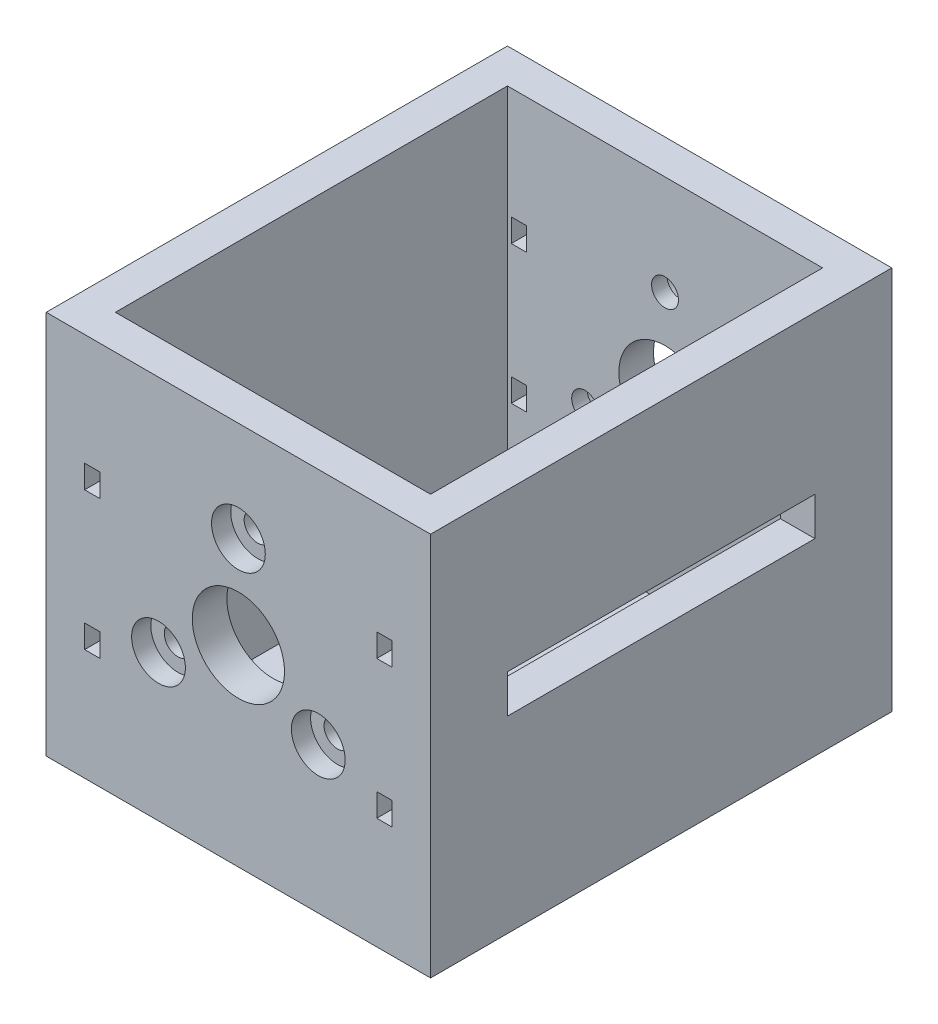
SolidWorks part; units mm, degrees
ref_plane "Front Plane" through (0, 0, 0) normal (0, 0, 1) x (1, 0, 0)
ref_plane "Top Plane" through (0, 0, 0) normal (0, 1, 0) x (1, 0, 0)
ref_plane "Right Plane" through (0, 0, 0) normal (1, 0, 0) x (0, 0, -1)
sketch "Sketch1" plane through (0, 0, 0) normal (0, 0, 1) x (1, 0, 0)
  line L1 (25, -25) -> (-25, -25)
  line L2 (25, -25) -> (25, 25)
  line L3 (25, 25) -> (-25, 25)
  line L4 (-25, -25) -> (-25, 25)
  line L5 (25, -25) -> (-25, 25) construction
  line L6 (25, 25) -> (-25, -25) construction
  point P0 (0, 0)
  dimension "D1" = 50
  dimension "D2" = 50
extrude "Boss-Extrude1" add sketch "Sketch1" along normal mid plane 60
ref_plane "Plane1" through (0, 0, 30) normal (0, 0, 1) x (1, 0, 0)
sketch "Sketch3" plane through (0, 0, 30) normal (0, 0, 1) x (1, 0, 0)
  circle A0 centre (0, 0) radius 6
  dimension "D1" = 12
extrude "Cut-Extrude1" cut sketch "Sketch3" against normal blind 70
sketch "Sketch4" plane through (0, 0, 30) normal (0, 0, 1) x (1, 0, 0)
  line L0 (-23.4706, 0) -> (22.7036, 0) construction
  line L1 (0, 23.8924) -> (0, -23.1254) construction
  line L3 (12, -0.5) -> (17, -0.5)
  line L4 (12, -0.5) -> (12, 0.5)
  line L5 (12, 0.5) -> (17, 0.5)
  line L6 (17, -0.5) -> (17, 0.5)
  line L7 (12, -0.5) -> (17, 0.5) construction
  line L8 (12, 0.5) -> (17, -0.5) construction
  point P5 (14.5, 0)
  dimension "D1" = 5
  dimension "D2" = 1
  dimension "D3" = 12
extrude "Cut-Extrude2" [suppressed] cut sketch "Sketch4" against normal blind 70
pattern_circular "CirPattern1" [suppressed] count 4 over 360
ref_plane "Plane2" through (0, 25, 0) normal (0, 1, 0) x (1, 0, 0)
sketch "Sketch5" plane through (0, 25, 0) normal (0, 1, 0) x (1, 0, 0)
  line L1 (20.5, -25.5) -> (-20.5, -25.5)
  line L2 (20.5, -25.5) -> (20.5, 25.5)
  line L3 (20.5, 25.5) -> (-20.5, 25.5)
  line L4 (-20.5, -25.5) -> (-20.5, 25.5)
  line L5 (20.5, -25.5) -> (-20.5, 25.5) construction
  line L6 (20.5, 25.5) -> (-20.5, -25.5) construction
  point P0 (0, 0)
  dimension "D1" = 41
  dimension "D2" = 51
extrude "Cut-Extrude3" cut sketch "Sketch5" against normal blind 48
sketch "Sketch6" plane through (0, 0, 30) normal (0, 0, 1) x (1, 0, 0)
  line L0 (0, 21.2323) -> (0, -19.4194) construction
  line L1 (-20.012, 0) -> (20.9882, 0) construction
  circle A0 centre (10, 0) radius 1.75
  dimension "D1" = 3.5
  dimension "D2" = 10
extrude "Cut-Extrude4" [suppressed] cut sketch "Sketch6" against normal blind 70
pattern_circular "CirPattern2" [suppressed] count 4 over 360
sketch "Sketch7" plane through (0, 0, 30) normal (0, 0, 1) x (1, 0, 0)
  line L0 (0, 18.3037) -> (0, -15.3054) construction
  line L1 (-19.4542, 0) -> (23.0801, 0) construction
  circle A0 centre (0, 12) radius 1.75
  dimension "D1" = 3.5
  dimension "D2" = 12
extrude "Cut-Extrude5" cut sketch "Sketch7" against normal blind 60
pattern_circular "CirPattern3" count 3 over 360 about axis through (0, 0, 0) along (0, 0, 1) of "Cut-Extrude5"
sketch "Sketch8" plane through (0, 0, 30) normal (0, 0, 1) x (1, 0, 0)
  line L1 (18, 10.5) -> (20, 10.5)
  line L2 (18, 10.5) -> (18, 7.5)
  line L3 (18, 7.5) -> (20, 7.5)
  line L4 (20, 10.5) -> (20, 7.5)
  line L5 (18, 10.5) -> (20, 7.5) construction
  line L6 (18, 7.5) -> (20, 10.5) construction
  point P0 (19, 9)
  dimension "D1" = 3
  dimension "D2" = 2
  dimension "D3" = 19
  dimension "D4" = 7.5
extrude "Cut-Extrude6" cut sketch "Sketch8" against normal blind 60
mirror "Mirror1" about plane through (0, 0, 0) normal (0, 1, 0) of "Cut-Extrude6" second plane through (0, 0, 0) second plane normal (1, 0, 0)
ref_plane "Plane3" through (25, 0, 0) normal (1, 0, 0) x (0, 0, -1)
sketch "Sketch9" plane through (25, 0, 0) normal (1, 0, 0) x (0, 0, -1)
  line L0 (0, 0) -> (0, 4) construction
  line L10 (20, 4.5) -> (-20, 4.5)
  line L11 (20, 4.5) -> (20, -0.5)
  line L12 (20, -0.5) -> (-20, -0.5)
  line L13 (-20, 4.5) -> (-20, -0.5)
  line L14 (20, 4.5) -> (-20, -0.5) construction
  line L15 (20, -0.5) -> (-20, 4.5) construction
  point P2 (0, 2)
  dimension "D1" = 40
  dimension "D2" = 5
  dimension "D3" = 2
extrude "Cut-Extrude7" cut sketch "Sketch9" against normal blind 40
ref_plane "Plane4" through (0, 0, 30) normal (0, 0, 1) x (1, 0, 0)
sketch "Sketch10" plane through (0, 0, 30) normal (0, 0, 1) x (1, 0, 0)
  circle A0 centre (0, 12) radius 3.5
  dimension "D1" = 7
extrude "Cut-Extrude8" cut sketch "Sketch10" against normal blind 2.5
pattern_circular "CirPattern4" count 3 over 360 about axis through (0, 0, 0) along (0, 0, 1) of "Cut-Extrude8"
mirror "Mirror2" about plane through (0, 0, 0) normal (0, 0, 1) of "CirPattern4", "Cut-Extrude8"
